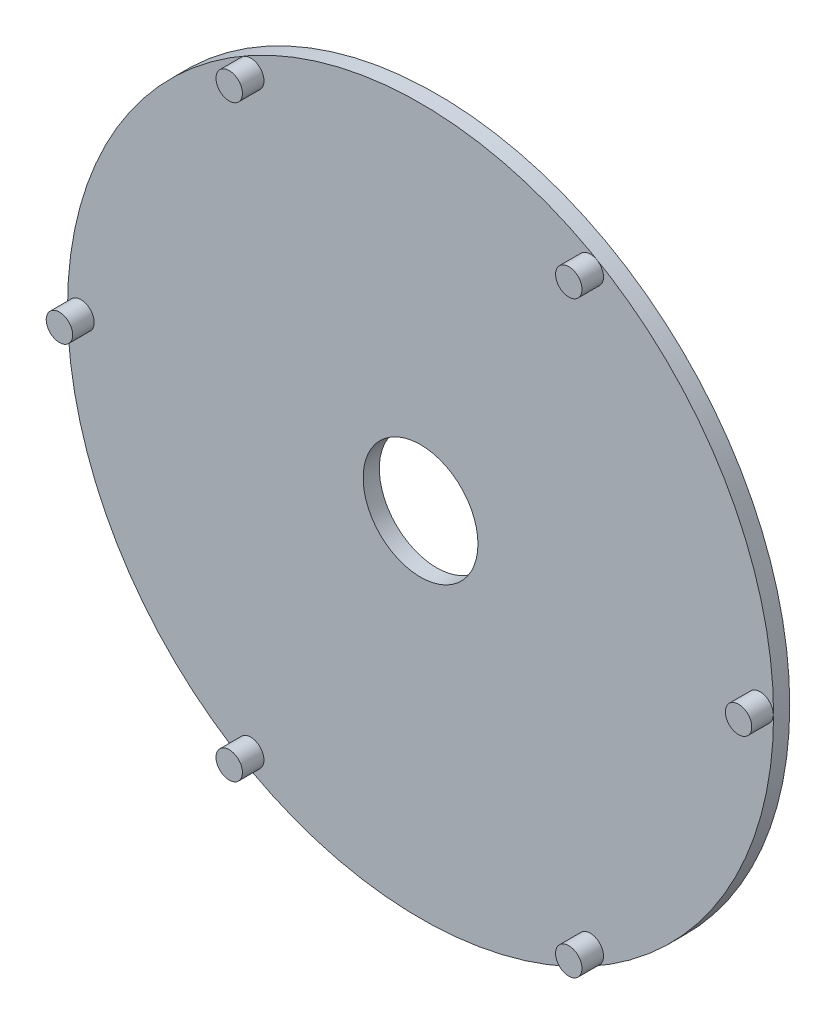
SolidWorks part; units mm, degrees
ref_plane "前视基准面" through (0, 0, 0) normal (0, 0, 1) x (1, 0, 0)
ref_plane "上视基准面" through (0, 0, 0) normal (0, 1, 0) x (1, 0, 0)
ref_plane "右视基准面" through (0, 0, 0) normal (1, 0, 0) x (0, 0, -1)
other "Configuration Table"
sketch "草图1" plane through (0, 0, 0) normal (0, 0, 1) x (1, 0, 0)
  circle A0 centre (0, 0) radius 65.5
  point P0 (0, 0)
  point P19 (0, 0)
  dimension "D1" = 131
extrude "凸台-拉伸1" add sketch "草图1" against normal blind 3 contours A0
sketch "草图2" plane through (0, 0, 0) normal (0, 0, 1) x (1, 0, 0)
  line L0 (0, 0) -> (-63, 0) construction
  circle A1 centre (-63, 0) radius 2.45
  circle A2 centre (-31.5, 54.5596) radius 2.45
  circle A3 centre (31.5, 54.5596) radius 2.45
  circle A4 centre (63, 0) radius 2.45
  circle A5 centre (31.5, -54.5596) radius 2.45
  circle A6 centre (-31.5, -54.5596) radius 2.45
  point P17 (0, 0)
  dimension "D1" = 4.9
  dimension "D2" = 63
  dimension "D3" = 6
extrude "凸台-拉伸2" add sketch "草图2" along normal blind 4
sketch "草图3" plane through (0, 0, 0) normal (0, 0, 1) x (1, 0, 0)
  circle A0 centre (0, 0) radius 10.65
  dimension "D1" = 21.3
extrude "切除-拉伸1" cut sketch "草图3" against normal through all
